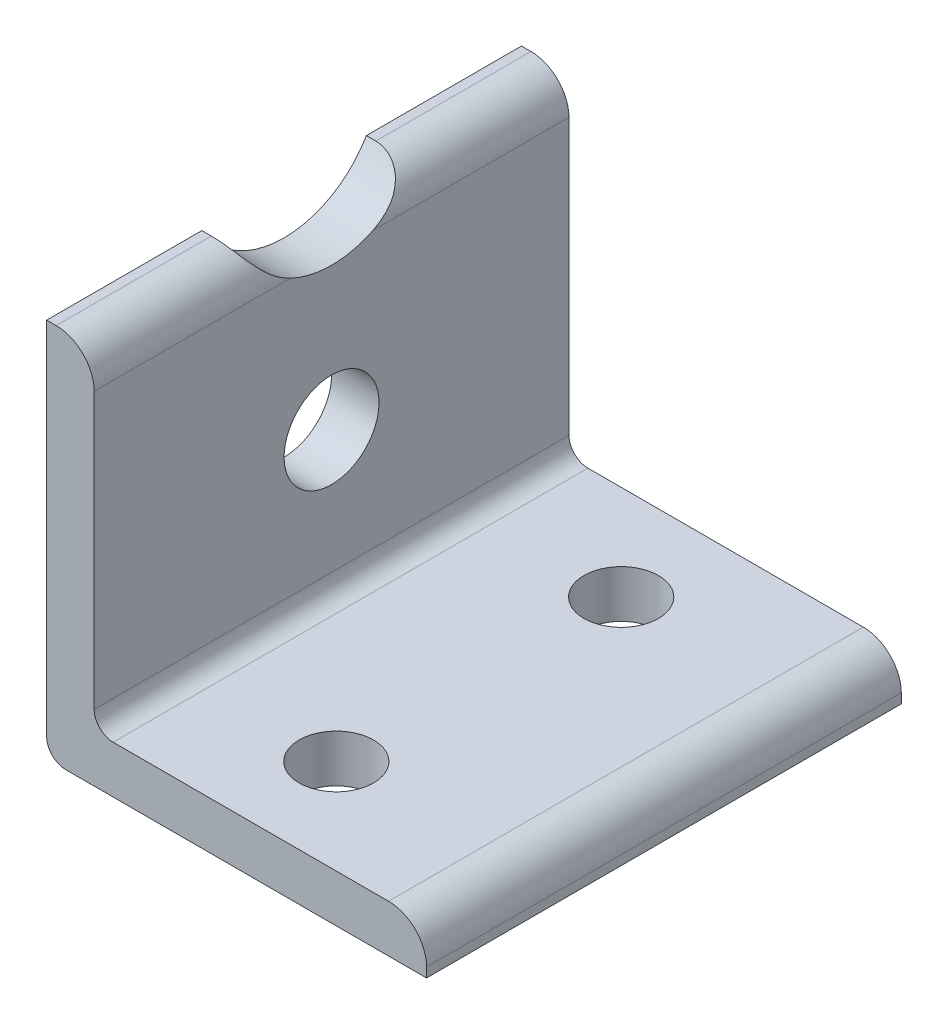
SolidWorks part; units mm, degrees
material "6061-T6 (SS)"
ref_plane "Front Plane" through (0, 0, 0) normal (0, 0, 1) x (1, 0, 0)
ref_plane "Top Plane" through (0, 0, 0) normal (0, 1, 0) x (1, 0, 0)
ref_plane "Right Plane" through (0, 0, 0) normal (1, 0, 0) x (0, 0, -1)
sketch "Sketch1" plane through (0, 0, 0) normal (0, 0, 1) x (1, 0, 0)
  line L0 (0, 0) -> (0, 25.4)
  line L1 (0, 25.4) -> (3.175, 25.4)
  line L2 (3.175, 25.4) -> (3.175, 3.175)
  line L3 (3.175, 3.175) -> (25.4, 3.175)
  line L4 (25.4, 3.175) -> (25.4, 0)
  line L5 (25.4, 0) -> (0, 0)
  dimension "D1" = 25.4
  dimension "D2" = 3.175
extrude "Boss-Extrude1" add sketch "Sketch1" along normal blind 31.75
fillet "Fillet1" radius 2.54 2 edges at (25.4, 3.175, 15.875) (3.175, 25.4, 15.875)
fillet "Fillet2" radius 1.27 2 edges at (0, 0, 15.875) (3.175, 3.175, 15.875)
sketch "Sketch2" plane through (0, 0, 0) normal (-1, 0, 0) x (0, 0, 1)
  line L0 (15.875, 0) -> (15.875, 28.575) construction
  line L1 (31.75, 0) -> (0, 0) construction
  circle A0 centre (15.875, 28.575) radius 6.35
  dimension "D2" = 12.7
  dimension "D1" = 28.575
extrude "Cut-Extrude1" cut sketch "Sketch2" against normal through all
sketch "Sketch3" plane through (0, 3.175, 0) normal (0, 1, 0) x (1, 0, 0)
  line L0 (13.0175, 0) -> (13.0175, -6.35) construction
  line L1 (22.86, 0) -> (4.445, 0) construction
  line L2 (13.0175, -6.35) -> (13.0175, -25.4) construction
  line L3 (13.0175, -25.4) -> (13.0175, -31.75) construction
  line L4 (22.86, -31.75) -> (4.445, -31.75) construction
  line L6 (0, -10.3757) -> (0, 0) construction
  circle A0 centre (13.0175, -6.35) radius 2.4892
  circle A1 centre (13.0175, -25.4) radius 2.4892
  dimension "D1" = 4.9784
  dimension "D2" = 6.35
  dimension "D3" = 13.0175
extrude "Cut-Extrude2" cut sketch "Sketch3" against normal through all
sketch "Sketch4" plane through (3.175, 0, 0) normal (1, 0, 0) x (0, 0, -1)
  line L0 (-15.875, 0) -> (-15.875, 12.7) construction
  line L1 (-31.75, 0) -> (0, 0) construction
  circle A0 centre (-15.875, 12.7) radius 3.175
  dimension "D1" = 6.35
  dimension "D2" = 12.7
extrude "Cut-Extrude3" cut sketch "Sketch4" against normal through all
